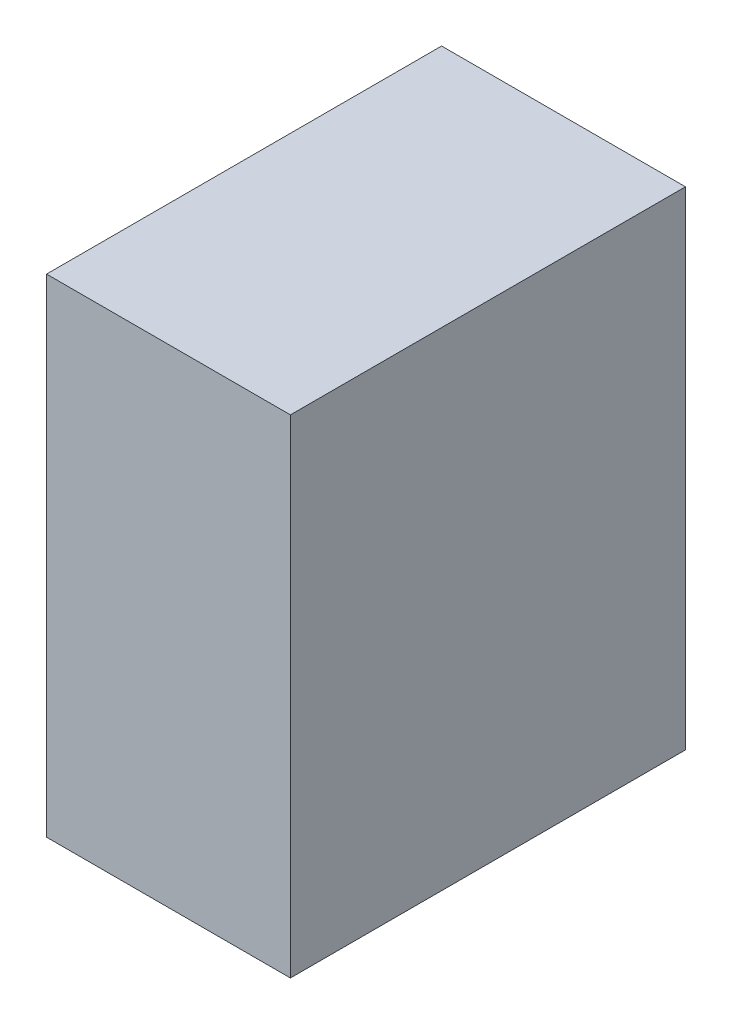
SolidWorks part; units mm, degrees
ref_plane "Front Plane" through (0, 0, 0) normal (0, 0, 1) x (1, 0, 0)
ref_plane "Top Plane" through (0, 0, 0) normal (0, 1, 0) x (1, 0, 0)
ref_plane "Right Plane" through (0, 0, 0) normal (1, 0, 0) x (0, 0, -1)
sketch "Sketch1" plane through (0, 0, 0) normal (1, 0, 0) x (0, 0, -1)
  line L1 (0, 0) -> (16.2, 0)
  line L2 (0, 0) -> (0, 20)
  line L3 (0, 20) -> (16.2, 20)
  line L4 (16.2, 0) -> (16.2, 20)
extrude "Boss-Extrude1" add sketch "Sketch1" along normal blind 10
